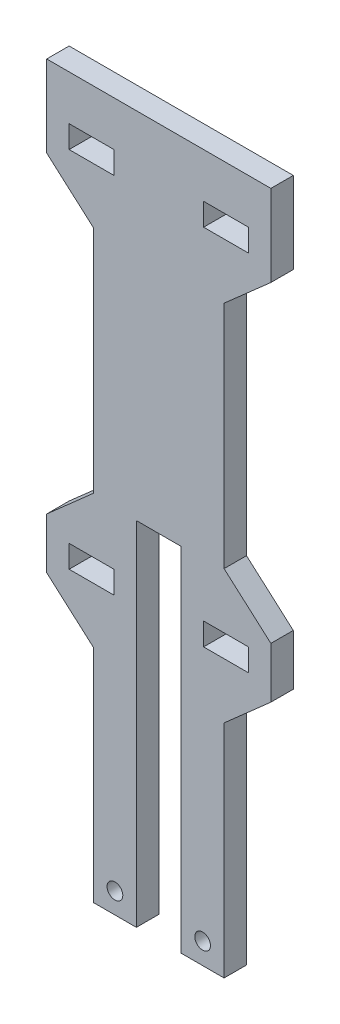
SolidWorks part; units mm, degrees
ref_plane "Front Plane" through (0, 0, 0) normal (0, 0, 1) x (1, 0, 0)
ref_plane "Top Plane" through (0, 0, 0) normal (0, 1, 0) x (1, 0, 0)
ref_plane "Right Plane" through (0, 0, 0) normal (1, 0, 0) x (0, 0, -1)
sketch "Sketch1" plane through (0, 0, 0) normal (0, 0, 1) x (1, 0, 0)
  line L0 (-29.0414, 54.3321) -> (-35.0414, 54.3321) construction
  line L1 (-35.0414, 66.3321) -> (24.9586, 66.3321)
  line L2 (-35.0414, 66.3321) -> (-35.0414, 44.515)
  line L3 (-11.0414, -73.6679) -> (-11.0414, -122.9611)
  line L4 (24.9586, 66.3321) -> (24.9586, 44.515)
  line L5 (18.9586, 54.3321) -> (24.9586, 54.3321) construction
  line L6 (-17.0414, 54.3321) -> (6.9586, 54.3321) construction
  line L7 (-29.0414, 54.3321) -> (-17.0414, 54.3321)
  line L8 (0.9586, -73.6679) -> (0.9586, -28.6679)
  line L9 (0.9586, -28.6679) -> (-11.0414, -28.6679)
  line L10 (-11.0414, -73.6679) -> (-11.0414, -28.6679)
  line L11 (-29.0414, 54.3321) -> (-29.0414, 48.3321)
  line L12 (-29.0414, 48.3321) -> (-17.0414, 48.3321)
  line L13 (-17.0414, 54.3321) -> (-17.0414, 48.3321)
  line L14 (6.9586, 54.3321) -> (18.9586, 54.3321)
  line L15 (6.9586, 54.3321) -> (6.9586, 48.3321)
  line L16 (6.9586, 48.3321) -> (18.9586, 48.3321)
  line L17 (18.9586, 54.3321) -> (18.9586, 48.3321)
  line L18 (12.4306, -122.9611) -> (0.9586, -122.9611)
  line L19 (-11.0414, -73.6679) -> (-11.0414, -122.9611) construction
  line L20 (-5.0414, 66.3321) -> (-5.0414, -28.6679) construction
  line L21 (-17.0414, 54.3321) -> (-17.0414, 66.3321) construction
  line L22 (0.9586, -73.6679) -> (0.9586, -122.9611)
  line L23 (-11.0414, -122.9611) -> (-22.5135, -122.9611)
  line L24 (-22.5135, -122.9611) -> (-22.5135, -63.8281)
  line L25 (-22.5135, 33.4541) -> (-35.0414, 44.515)
  line L26 (24.9586, 44.515) -> (12.4306, 33.4541)
  line L27 (12.4306, 33.4541) -> (12.4306, -28.0722)
  line L28 (-22.5135, -28.0722) -> (-35.0414, -39.133)
  line L29 (-35.0414, -39.133) -> (-35.0414, -52.7673)
  line L30 (-35.0414, -52.7673) -> (-22.5135, -63.8281)
  line L31 (12.4306, -28.0722) -> (24.9586, -39.133)
  line L32 (24.9586, -39.133) -> (24.9586, -52.7673)
  line L33 (24.9586, -52.7673) -> (12.4306, -63.8281)
  line L34 (-17.0414, -42.9502) -> (6.9586, -42.9502) construction
  line L35 (-29.0414, -42.9502) -> (-17.0414, -42.9502)
  line L36 (-29.0414, -42.9502) -> (-29.0414, -48.9502)
  line L37 (-29.0414, -48.9502) -> (-17.0414, -48.9502)
  line L38 (-17.0414, -42.9502) -> (-17.0414, -48.9502)
  line L39 (6.9586, -42.9502) -> (18.9586, -42.9502)
  line L40 (6.9586, -42.9502) -> (6.9586, -48.9502)
  line L41 (6.9586, -48.9502) -> (18.9586, -48.9502)
  line L42 (18.9586, -42.9502) -> (18.9586, -48.9502)
  line L43 (-22.5135, -28.0722) -> (-22.5135, 33.4541)
  line L44 (12.4306, -63.8281) -> (12.4306, -122.9611)
  line L45 (18.9586, 48.3321) -> (18.9586, 39.2176) construction
  line L46 (18.9586, -48.9502) -> (18.9586, -58.0647) construction
  line L47 (6.9586, -42.9502) -> (6.9586, -28.6679) construction
  line L48 (-16.7774, -122.9611) -> (-16.7774, -117.3861) construction
  line L49 (6.6946, -117.277) -> (6.6946, -122.9611) construction
  circle A0 centre (-16.7774, -117.3861) radius 2.1
  circle A1 centre (6.6946, -117.277) radius 2.1
  point P0 (-5.0414, 66.3321)
  point P44 (-35.0414, -45.9502)
  point P45 (-29.0414, -45.9502)
extrude "Boss-Extrude1" add sketch "Sketch1" along normal blind 6
